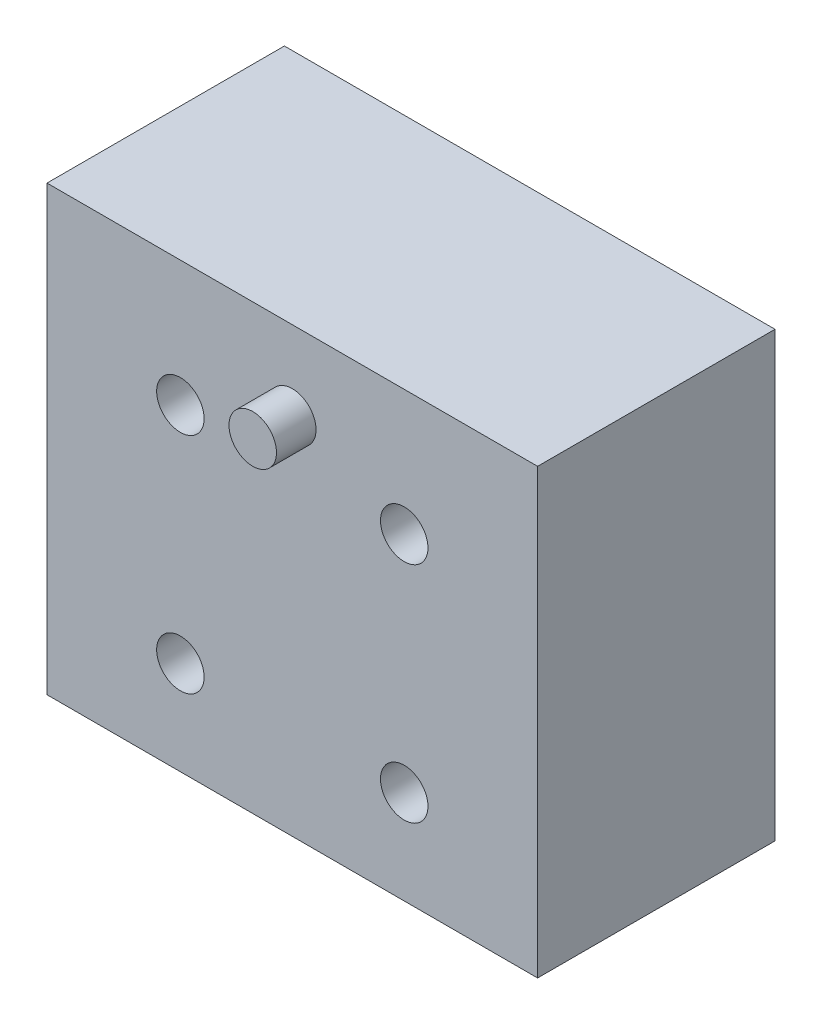
SolidWorks part; units mm, degrees
ref_plane "Plano frontal" through (0, 0, 0) normal (0, 0, 1) x (1, 0, 0)
ref_plane "Plano superior" through (0, 0, 0) normal (0, 1, 0) x (1, 0, 0)
ref_plane "Plano direito" through (0, 0, 0) normal (1, 0, 0) x (0, 0, -1)
sketch "Esboço1" plane through (0, 0, 0) normal (0, 0, 1) x (1, 0, 0)
  line L0 (0, 0) -> (-31.7939, 31.7939) construction
  line L1 (0, 0) -> (38.7026, 38.7026) construction
  line L2 (0, 0) -> (0, 47.703) construction
  line L3 (0, 0) -> (-33.7821, -33.7821) construction
  line L4 (0, 0) -> (48.905, -48.905) construction
  circle A0 centre (0, 0) radius 60
  circle A1 centre (0, 0) radius 20
  circle A2 centre (-14.1421, 14.1421) radius 3
  circle A3 centre (14.1421, 14.1421) radius 3
  circle A4 centre (14.1421, -14.1421) radius 3
  circle A5 centre (-14.1421, -14.1421) radius 3
  circle A6 centre (0, 20) radius 3
  point P4 (14.1421, 14.1421)
  point P10 (-14.1421, 14.1421)
  point P11 (14.1421, -14.1421)
  point P12 (-14.1421, -14.1421)
  dimension "D1" = 120
  dimension "D2" = 40
  dimension "D5" = 6
  dimension "D6" = 6
  dimension "D3" = 45
  dimension "D4" = 45
extrude "Ressalto-extrusão4" add sketch "Esboço1" against normal blind 30 contours A0 A6 A1 A3 A4 A5 A2 | A6 A1 A2 A5 A4 A3
sketch "Esboço6" plane through (0, 0, 0) normal (0, 0, 1) x (1, 0, 0)
  circle A0 centre (0, 0) radius 60
  circle A1 centre (-14.1421, -14.1421) radius 5
  circle A2 centre (14.1421, -14.1421) radius 5
  circle A3 centre (-14.1421, 14.1421) radius 5
  circle A4 centre (14.1421, 14.1421) radius 5
  dimension "D1" = 10
  dimension "D2" = 120
extrude "Ressalto-extrusão8" add sketch "Esboço6" against normal blind 30
sketch "Esboço9" plane through (0, 0, -30) normal (0, 0, -1) x (-1, 0, 0)
  line L19 (0, 0) -> (31, 0)
  line L20 (0, 0) -> (0, 30)
  line L21 (0, 30) -> (31, 30)
  line L22 (31, 0) -> (31, 30)
  line L23 (0, 0) -> (-31, 0)
  line L24 (0, 0) -> (0, 30)
  line L25 (0, 30) -> (-31, 30)
  line L26 (-31, 0) -> (-31, 30)
  line L27 (-31, 0) -> (31, 0)
  line L28 (-31, 0) -> (-31, -41)
  line L29 (-31, -41) -> (31, -41)
  line L30 (31, 0) -> (31, -41)
  line L31 (-31, -41) -> (31, -41)
  line L32 (-31, -41) -> (-31, -31)
  line L34 (31, -41) -> (31, -31)
  circle A1 centre (0, 0) radius 30
  circle A2 centre (0, 0) radius 60
  dimension "D3" = 31
  dimension "D1" = 60
  dimension "D2" = 31
  dimension "D4" = 30
  dimension "D5" = 41
extrude "Corte-extrusão1" cut sketch "Esboço9" against normal through all
sketch "Esboço11" plane through (0, 0, 0) normal (0, 0, 1) x (1, 0, 0)
  line L0 (31, -41) -> (31, 30) construction
  line L1 (-31, -41) -> (31, -41)
  line L2 (-31, -41) -> (-31, -26)
  line L3 (-31, -26) -> (31, -26)
  line L4 (31, -41) -> (31, -26)
  dimension "D1" = 15
extrude "Corte-extrusão2" cut sketch "Esboço11" against normal through all
sketch "Esboço12" plane through (0, -26, 0) normal (0, -1, 0) x (1, 0, 0)
  line L0 (31, -30) -> (31, 0) construction
  line L1 (31, -30) -> (-31, -30) construction
  line L2 (-31, -30) -> (-31, 0) construction
  circle A0 centre (24.07, -15) radius 2.5
  circle A1 centre (0, -15) radius 2.5
  circle A2 centre (-24.07, -15) radius 2.5
  dimension "D1" = 5
  dimension "D2" = 5
  dimension "D3" = 5
  dimension "D4" = 31
  dimension "D5" = 15
  dimension "D6" = 15
  dimension "D7" = 15
  dimension "D8" = 6.93
  dimension "D9" = 6.93
extrude "Corte-extrusão3" cut sketch "Esboço12" against normal blind 15
sketch "Esboço15" plane through (0, 0, 0) normal (0, 0, 1) x (1, 0, 0)
  line L0 (-31, 30) -> (31, 30) construction
  line L1 (31, 30) -> (31, -26) construction
  circle A0 centre (0, 20) radius 3
  dimension "D1" = 6
  dimension "D2" = 10
  dimension "D3" = 31
extrude "Ressalto-extrusão9" add sketch "Esboço15" along normal blind 5
sketch "Esboço16" plane through (0, 0, -30) normal (0, 0, -1) x (-1, 0, 0)
  circle A0 centre (14.1421, 14.1421) radius 4.75
  circle A1 centre (14.1421, -14.1421) radius 4.75
  circle A2 centre (-14.1421, 14.1421) radius 4.75
  circle A3 centre (-14.1421, -14.1421) radius 4.75
  dimension "D1" = 9.5
  dimension "D2" = 9.5
  dimension "D3" = 9.5
  dimension "D4" = 9.5
extrude "Corte-extrusão4" cut sketch "Esboço16" against normal blind 6 contours A0 | A1 | A3 | A2
